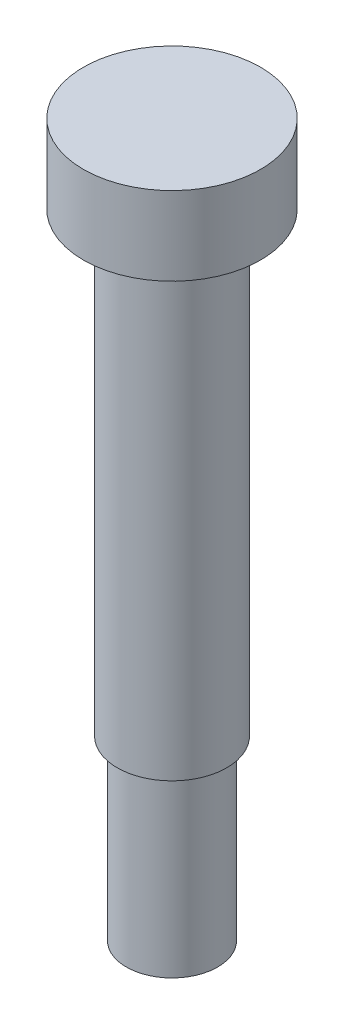
SolidWorks part; units mm, degrees
ref_plane "前视基准面" through (0, 0, 0) normal (0, 0, 1) x (1, 0, 0)
ref_plane "上视基准面" through (0, 0, 0) normal (0, 1, 0) x (1, 0, 0)
ref_plane "右视基准面" through (0, 0, 0) normal (1, 0, 0) x (0, 0, -1)
sketch "草图1" plane through (0, 0, 0) normal (0, 1, 0) x (1, 0, 0)
  circle A0 centre (0, 0) radius 4.85
  dimension "D1" = 9.7
extrude "凸台-拉伸1" add sketch "草图1" along normal blind 4.3
sketch "草图2" plane through (0, 0, 0) normal (0, -1, 0) x (1, 0, 0)
  circle A0 centre (0, 0) radius 3
  dimension "D1" = 6
extrude "凸台-拉伸2" add sketch "草图2" along normal blind 25
sketch "草图3" plane through (0, -25, 0) normal (0, -1, 0) x (1, 0, 0)
  circle A0 centre (0, 0) radius 2.5
  dimension "D1" = 5
extrude "凸台-拉伸3" add sketch "草图3" along normal blind 9.7
cosmetic thread "装饰螺纹线1" parameters "D2"=4
